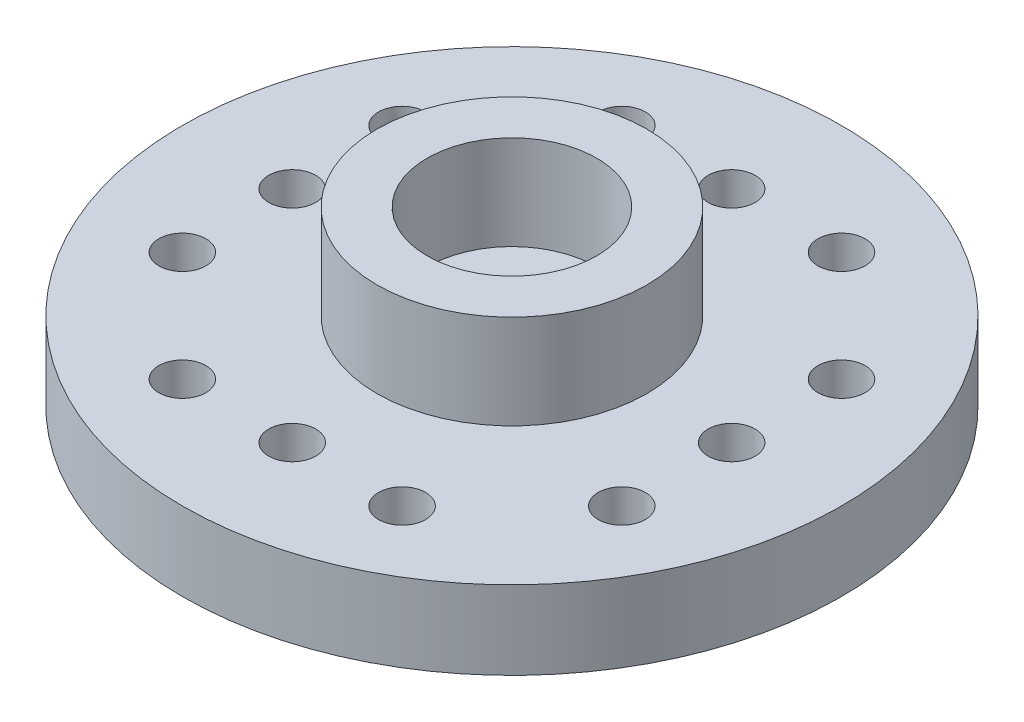
SolidWorks part; units mm, degrees
ref_plane "Front Plane" through (0, 0, 0) normal (0, 0, 1) x (1, 0, 0)
ref_plane "Top Plane" through (0, 0, 0) normal (0, 1, 0) x (1, 0, 0)
ref_plane "Right Plane" through (0, 0, 0) normal (1, 0, 0) x (0, 0, -1)
sketch "Sketch1" plane through (0, 0, 0) normal (0, 1, 0) x (1, 0, 0)
  circle A0 centre (0, 0) radius 1.5
  circle A1 centre (0, 0) radius 10.5
  dimension "D1" = 3
  dimension "D2" = 21
extrude "Boss-Extrude1" add sketch "Sketch1" along normal blind 2.5
sketch "Sketch2" plane through (0, 2.5, 0) normal (0, 1, 0) x (1, 0, 0)
  circle A0 centre (0, 0) radius 4.3
  circle A1 centre (0, 0) radius 2.7
  dimension "D1" = 5.4
  dimension "D2" = 8.6
extrude "Boss-Extrude2" add sketch "Sketch2" along normal blind 3
sketch "Sketch3" plane through (0, 2.5, 0) normal (0, 1, 0) x (1, 0, 0)
  circle A0 centre (0, 7) radius 0.75
  circle A1 centre (3.5, 7) radius 0.75
  circle A2 centre (-3.5, 7) radius 0.75
  point P6 (0, 0)
  point P8 (3.7256, 6.9964)
  point P9 (0, 0)
  dimension "D1" = 7
  dimension "D2" = 1.5
  dimension "D3" = 3.5
  dimension "D4" = 3.5
extrude "Cut-Extrude1" cut sketch "Sketch3" against normal through all
pattern_circular "CirPattern1" count 4 every 90 about axis through (0, 0, 0) along (0, 1, 0) of "Cut-Extrude1"
sketch "Sketch4" plane through (0, 0, 0) normal (0, -1, 0) x (1, 0, 0)
  circle A0 centre (0, 0) radius 2.2
  circle A1 centre (0, 0) radius 2.7
  circle A2 centre (0, 0) radius 4.3
  circle M14 centre (0, 0) radius 1.5
  dimension "D1" = 8.6
  dimension "D2" = 5.4
  dimension "D3" = 4.4
extrude "Cut-Extrude2" cut sketch "Sketch4" against normal blind 1 contours A0 M14 | A2 A1
